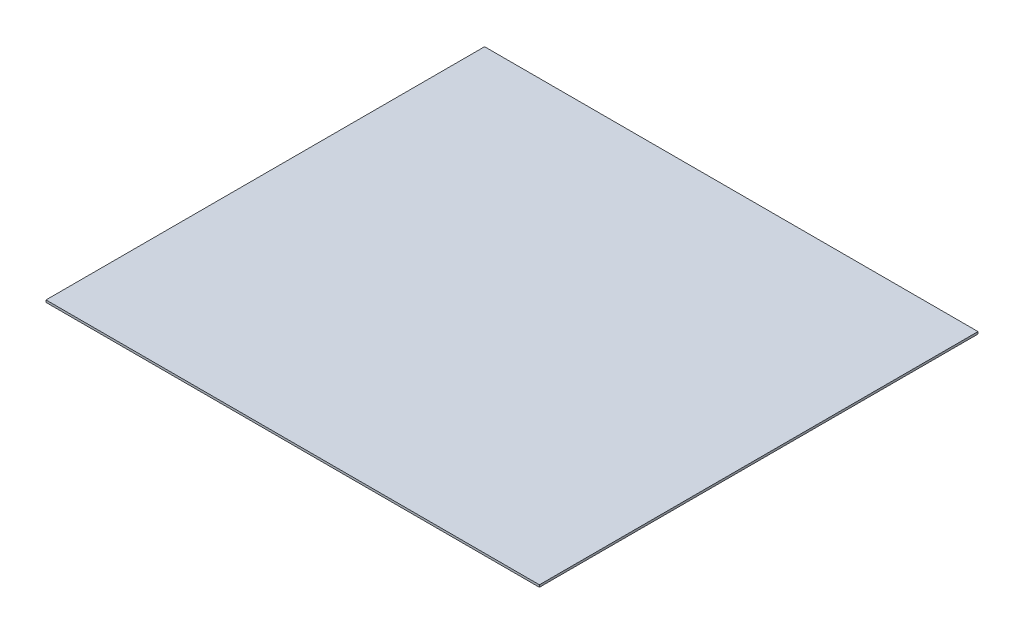
SolidWorks part; units mm, degrees
material "7075-T6 (SN)"
ref_plane "Front Plane" through (0, 0, 0) normal (0, 0, 1) x (1, 0, 0)
ref_plane "Top Plane" through (0, 0, 0) normal (0, 1, 0) x (1, 0, 0)
ref_plane "Right Plane" through (0, 0, 0) normal (1, 0, 0) x (0, 0, -1)
ref_plane "Plane1" through (0, -50, 0) normal (0, 1, 0) x (1, 0, 0)
sketch "Sketch1" plane through (0, -50, 0) normal (0, 1, 0) x (1, 0, 0)
  line L1 (-225, 200) -> (225, 200)
  line L2 (-225, 200) -> (-225, -200)
  line L3 (-225, -200) -> (225, -200)
  line L4 (225, 200) -> (225, -200)
  line L5 (-225, 200) -> (225, -200) construction
  line L6 (-225, -200) -> (225, 200) construction
  point P0 (0, 0)
  dimension "D1" = 450
  dimension "D2" = 400
extrude "Boss-Extrude1" add sketch "Sketch1" along normal blind 2
